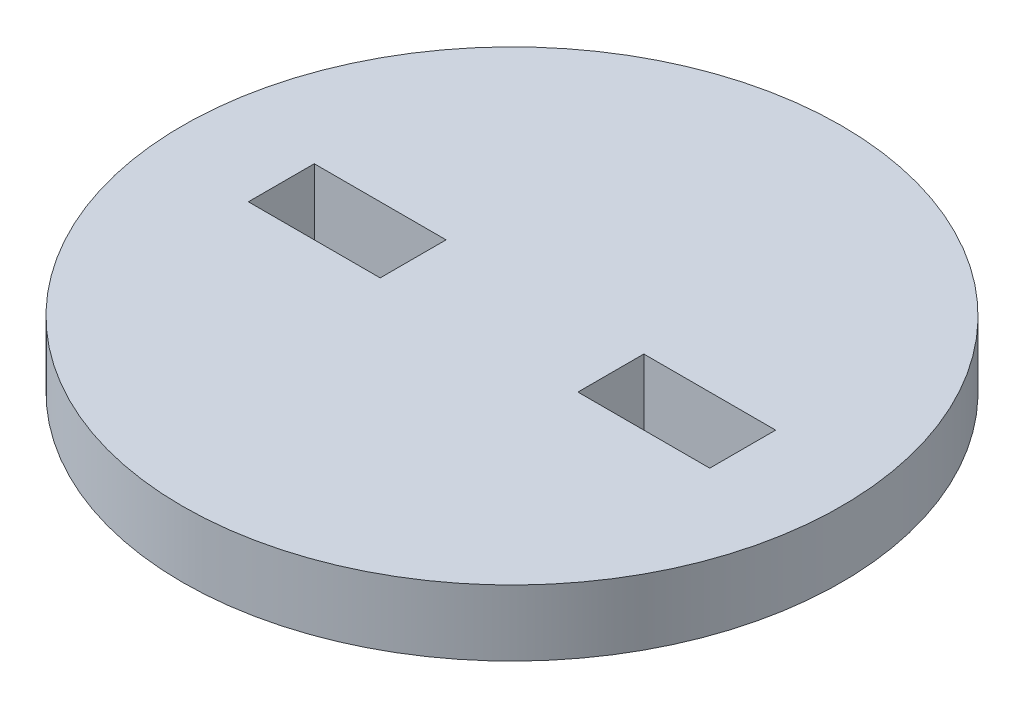
SolidWorks part; units mm, degrees
ref_plane "Front Plane" through (0, 0, 0) normal (0, 0, 1) x (1, 0, 0)
ref_plane "Top Plane" through (0, 0, 0) normal (0, 1, 0) x (1, 0, 0)
ref_plane "Right Plane" through (0, 0, 0) normal (1, 0, 0) x (0, 0, -1)
sketch "Sketch1" plane through (0, 0, 0) normal (0, 1, 0) x (1, 0, 0)
  line L0 (-20, 0) -> (33.8827, 0) construction
  line L1 (0, 0) -> (0, -6.7859) construction
  line L2 (-14, 2) -> (-6, 2)
  line L3 (-14, 2) -> (-14, -2)
  line L4 (-14, -2) -> (-6, -2)
  line L5 (-6, 2) -> (-6, -2)
  line L6 (-14, 2) -> (-6, -2) construction
  line L7 (-14, -2) -> (-6, 2) construction
  line L8 (14, -2) -> (6, 2) construction
  line L9 (14, 2) -> (6, -2) construction
  line L10 (6, 2) -> (6, -2)
  line L11 (14, -2) -> (6, -2)
  line L12 (14, 2) -> (14, -2)
  line L13 (14, 2) -> (6, 2)
  circle A0 centre (0, 0) radius 20
  point P5 (-10, 0)
  point P15 (10, 0)
  dimension "D1" = 40
  dimension "D2" = 8
  dimension "D3" = 4
  dimension "D4" = 6
extrude "Boss-Extrude1" add sketch "Sketch1" along normal blind 4
